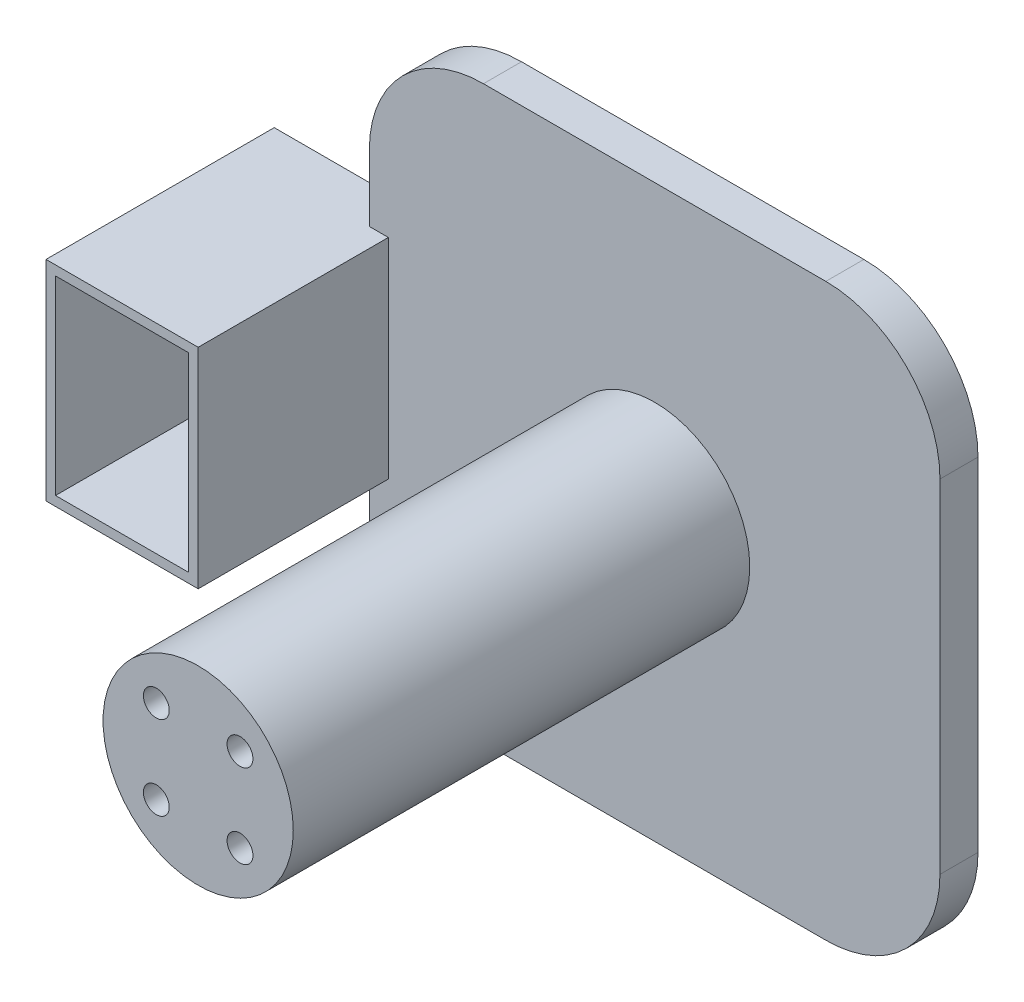
SolidWorks part; units mm, degrees
ref_plane "前视基准面" through (0, 0, 0) normal (0, 0, 1) x (1, 0, 0)
ref_plane "上视基准面" through (0, 0, 0) normal (0, 1, 0) x (1, 0, 0)
ref_plane "右视基准面" through (0, 0, 0) normal (1, 0, 0) x (0, 0, -1)
other "Configuration Table"
sketch "草图1" plane through (0, 0, 0) normal (0, 0, 1) x (1, 0, 0)
  line L1 (30, 0) -> (120, 0)
  line L2 (0, 30) -> (0, 120)
  line L3 (30, 150) -> (120, 150)
  line L4 (150, 30) -> (150, 120)
  arc A0 (150, 120) -> (120, 150) centre (120, 120) ccw
  arc A1 (120, 0) -> (150, 30) centre (120, 30) ccw
  arc A2 (0, 30) -> (30, 0) centre (30, 30) ccw
  arc A3 (0, 120) -> (30, 150) centre (30, 120) cw
  point P9 (150, 0)
  point P12 (0, 0)
  point P15 (0, 150)
  dimension "D3" = 30
  dimension "D1" = 150
  dimension "D2" = 150
extrude "凸台-拉伸1" add sketch "草图1" along normal blind 10
sketch "草图2" plane through (0, 0, 10) normal (0, 0, 1) x (1, 0, 0)
  line L0 (30, 120) -> (120, 30)
  line L4 (120, 150) -> (30, 150)
  line L5 (0, 120) -> (0, 30)
  line L6 (30, 0) -> (120, 0)
  line L7 (150, 30) -> (150, 120)
  line L8 (120, 150) -> (30, 150)
  line L9 (0, 120) -> (0, 30)
  line L10 (30, 0) -> (120, 0)
  line L11 (150, 30) -> (150, 120)
  circle A0 centre (75, 75) radius 25
  arc A4 (150, 120) -> (120, 150) centre (120, 120) ccw
  arc A5 (30, 150) -> (0, 120) centre (30, 120) ccw
  arc A6 (0, 30) -> (30, 0) centre (30, 30) ccw
  arc A7 (120, 0) -> (150, 30) centre (120, 30) ccw
  arc A8 (150, 120) -> (120, 150) centre (120, 120) ccw
  arc A9 (30, 150) -> (0, 120) centre (30, 120) ccw
  arc A10 (0, 30) -> (30, 0) centre (30, 30) ccw
  arc A11 (120, 0) -> (150, 30) centre (120, 30) ccw
  dimension "D2" = 50
  dimension "D1" = 0
extrude "凸台-拉伸2" add sketch "草图2" along normal blind 120 contours L0 A0 | L0 A0
sketch "草图5" plane through (0, 0, 130) normal (0, 0, 1) x (1, 0, 0)
  line L1 (64, 64) -> (86, 64)
  line L2 (64, 64) -> (64, 86)
  line L3 (64, 86) -> (86, 86)
  line L4 (86, 64) -> (86, 86)
  line L5 (64, 64) -> (86, 86) construction
  line L6 (64, 86) -> (86, 64) construction
  circle A0 centre (64, 86) radius 3.4
  circle A1 centre (75, 75) radius 25
  circle A2 centre (75, 75) radius 25
  circle A3 centre (64, 64) radius 3.4
  circle A4 centre (86, 86) radius 3.4
  circle A5 centre (86, 64) radius 3.4
  dimension "D4" = 6.8
  dimension "D5" = 6.8
  dimension "D6" = 6.8
  dimension "D7" = 6.8
  dimension "D2" = 22
  dimension "D3" = 22
  dimension "D1" = 0
extrude "切除-拉伸1" cut sketch "草图5" against normal blind 10 contours L2 A0 L3 | L3 A0 L2 | L2 A3 L1 | L1 A3 L2 | L1 A5 L4 | L4 A5 L1 | L4 A4 L3 | L3 A4 L4
sketch "草图7" plane through (0, 0, 10) normal (0, 0, 1) x (1, 0, 0)
  line L1 (-35, 102.5) -> (5, 102.5)
  line L2 (-35, 102.5) -> (-35, 47.5)
  line L3 (-35, 47.5) -> (5, 47.5)
  line L4 (5, 102.5) -> (5, 47.5)
  line L5 (0, 75) -> (36.039, 75)
  line L6 (0, 120) -> (0, 30) construction
  circle A2 centre (75, 75) radius 25
  circle A3 centre (75, 75) radius 25
  line M7 (0, 120) -> (0, 30)
  dimension "D2" = 70
  dimension "D1" = 0
  dimension "D3" = 55
  dimension "D4" = 40
  dimension "D5" = 27.5
extrude "凸台-拉伸3" add sketch "草图7" against normal through all contours L2 L3 L1 M7
sketch "草图8" plane through (0, 0, 10) normal (0, 0, 1) x (1, 0, 0)
  line L0 (-35, 102.5) -> (0, 102.5) construction
  line L1 (-35, 102.5) -> (-35, 47.5) construction
  line L2 (-35, 47.5) -> (0, 47.5) construction
  line L3 (2.5, 100) -> (2.5, 50)
  line L4 (-35, 102.5) -> (0, 102.5)
  line L5 (-35, 102.5) -> (-35, 47.5)
  line L6 (-35, 47.5) -> (0, 47.5)
  line L7 (0, 102.5) -> (5, 102.5)
  line L8 (5, 102.5) -> (5, 47.5)
  line L9 (5, 47.5) -> (0, 47.5)
  line L26 (2.5, 100) -> (-32.5, 100)
  line L27 (-32.5, 100) -> (-32.5, 50)
  line L28 (-32.5, 50) -> (2.5, 50)
  dimension "D1" = 2.5
  dimension "D2" = 2.5
  dimension "D3" = 2.5
  dimension "D4" = 35
  dimension "D5" = 2.5
extrude "凸台-拉伸4" add sketch "草图8" along normal blind 50
